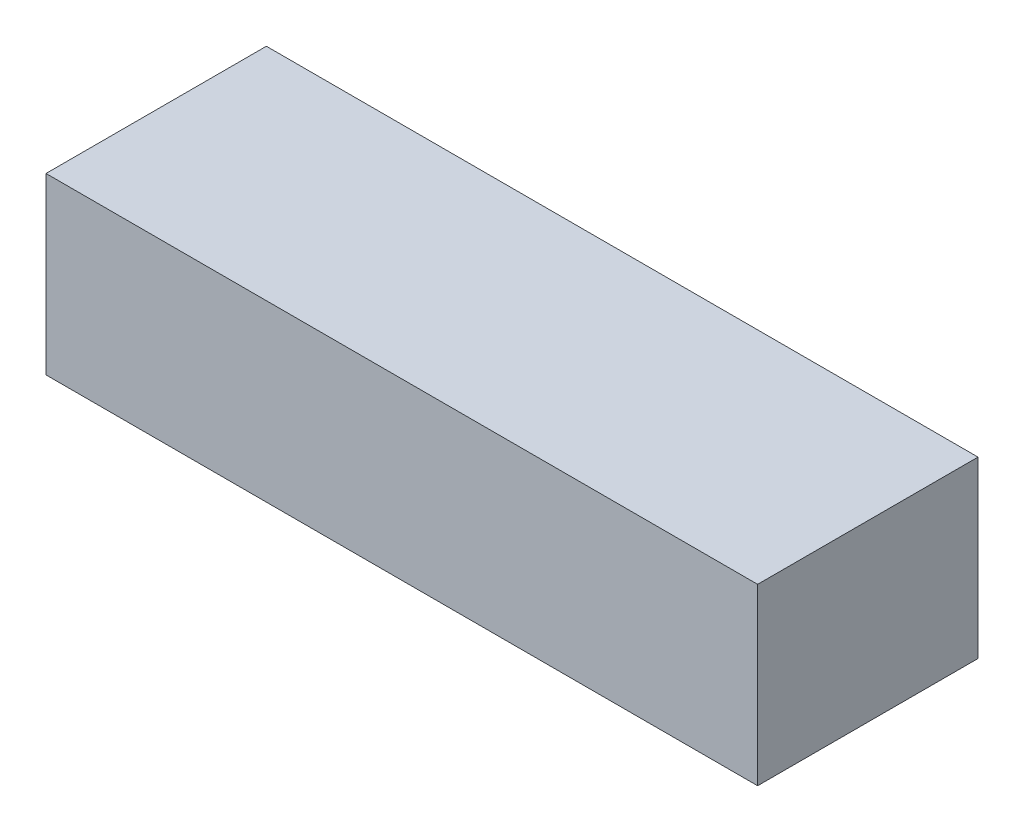
SolidWorks part; units mm, degrees
ref_plane "Front Plane" through (0, 0, 0) normal (0, 0, 1) x (1, 0, 0)
ref_plane "Top Plane" through (0, 0, 0) normal (0, 1, 0) x (1, 0, 0)
ref_plane "Right Plane" through (0, 0, 0) normal (1, 0, 0) x (0, 0, -1)
sketch "Sketch1" plane through (0, 0, 0) normal (0, 1, 0) x (1, 0, 0)
  line L1 (-77.5, 24) -> (77.5, 24)
  line L2 (-77.5, 24) -> (-77.5, -24)
  line L3 (-77.5, -24) -> (77.5, -24)
  line L4 (77.5, 24) -> (77.5, -24)
  line L5 (-77.5, 24) -> (77.5, -24) construction
  line L6 (-77.5, -24) -> (77.5, 24) construction
  point P4 (0, 0)
  point P5 (0, 0)
  dimension "D1" = 155
  dimension "D2" = 48
extrude "Boss-Extrude1" add sketch "Sketch1" along normal blind 38
